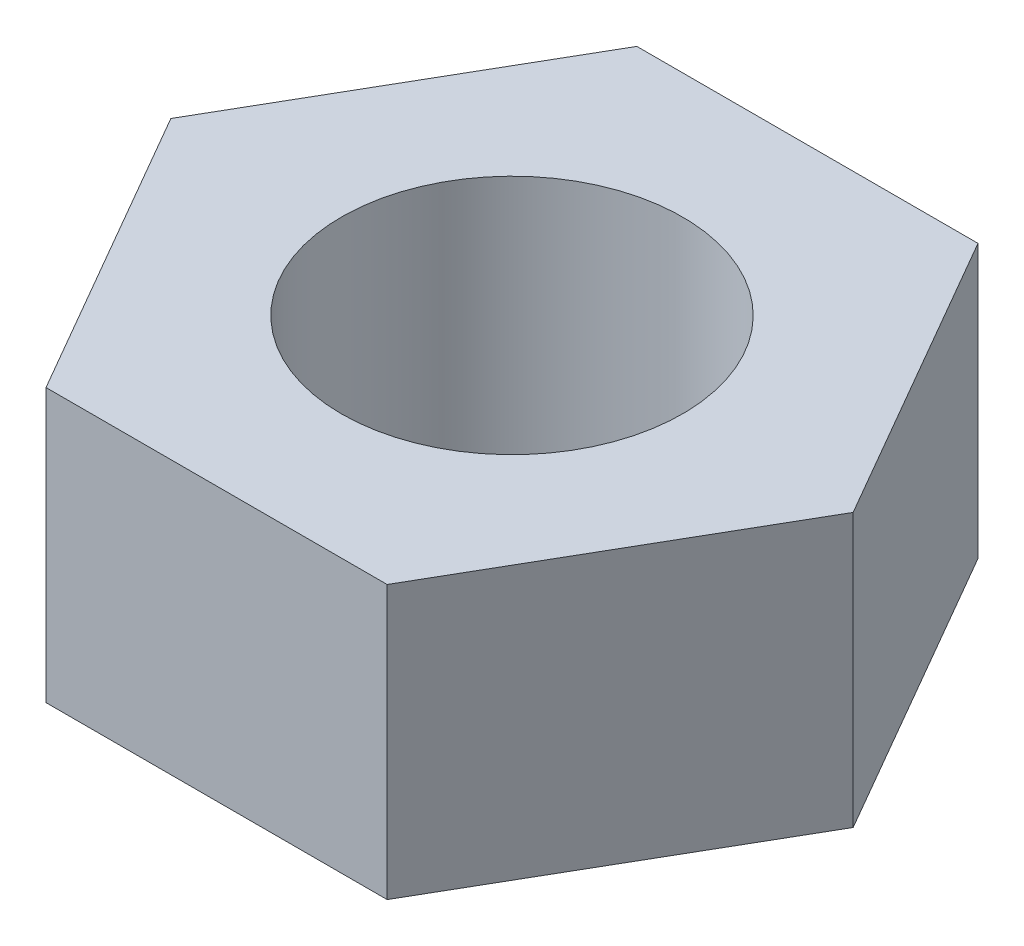
SolidWorks part; units mm, degrees
material "0.6020 (EN-GJL-200)"
ref_plane "前视基准面" through (0, 0, 0) normal (0, 0, 1) x (1, 0, 0)
ref_plane "上视基准面" through (0, 0, 0) normal (0, 1, 0) x (1, 0, 0)
ref_plane "右视基准面" through (0, 0, 0) normal (1, 0, 0) x (0, 0, -1)
other "Configuration Table"
sketch "草图1" plane through (0, 0, 0) normal (0, 1, 0) x (1, 0, 0)
  line L1 (1.25, 2.1651) -> (-1.25, 2.1651)
  line L2 (-1.25, 2.1651) -> (-2.5, 0)
  line L3 (-2.5, 0) -> (-1.25, -2.1651)
  line L4 (-1.25, -2.1651) -> (1.25, -2.1651)
  line L5 (1.25, -2.1651) -> (2.5, 0)
  line L6 (2.5, 0) -> (1.25, 2.1651)
  circle A0 centre (0, 0) radius 2.1651 construction
  circle A1 centre (0, 0) radius 1.25
  dimension "D1" = 2.5
  dimension "D2" = 2.5
extrude "凸台-拉伸1" add sketch "草图1" along normal blind 2
